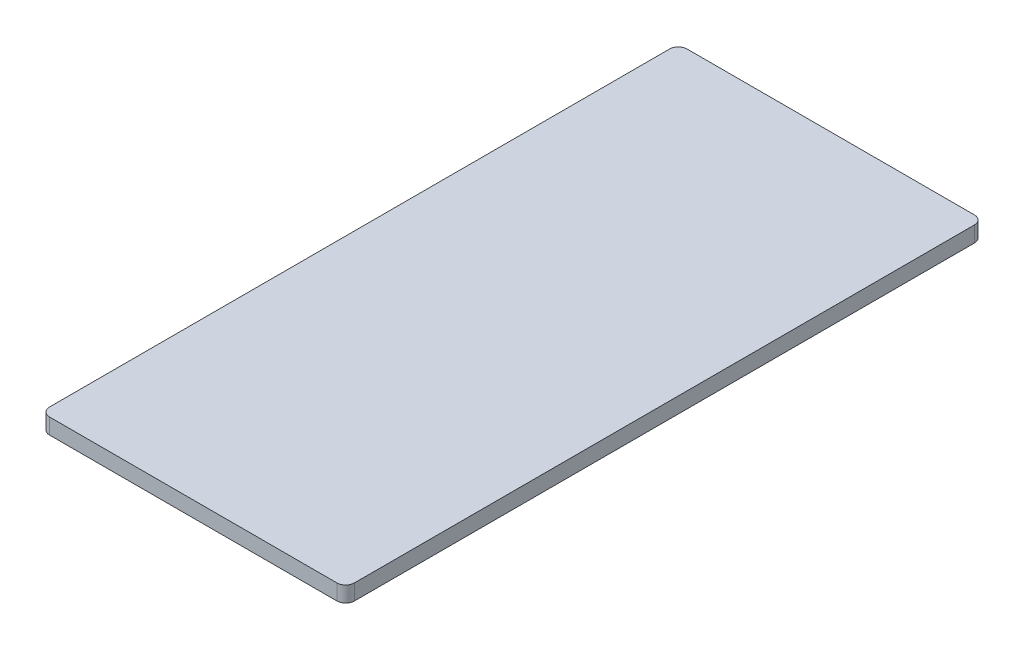
SolidWorks part; units mm, degrees
ref_plane "前视基准面" through (0, 0, 0) normal (0, 0, 1) x (1, 0, 0)
ref_plane "上视基准面" through (0, 0, 0) normal (0, 1, 0) x (1, 0, 0)
ref_plane "右视基准面" through (0, 0, 0) normal (1, 0, 0) x (0, 0, -1)
other "Configuration Table"
sketch "草图1" plane through (0, 0, 0) normal (0, 1, 0) x (1, 0, 0)
  line L1 (-175, -366) -> (175, -366)
  line L2 (-175, -366) -> (-175, 366)
  line L3 (-175, 366) -> (175, 366)
  line L4 (175, -366) -> (175, 366)
  point P4 (-175, 0)
  point P6 (0, 366)
  dimension "D1" = 732
  dimension "D2" = 350
extrude "凸台-拉伸1" add sketch "草图1" along normal blind 18
fillet "圆角1" radius 10 4 edges at (-175, 9, -366) (175, 9, -366) (175, 9, 366) (-175, 9, 366)
